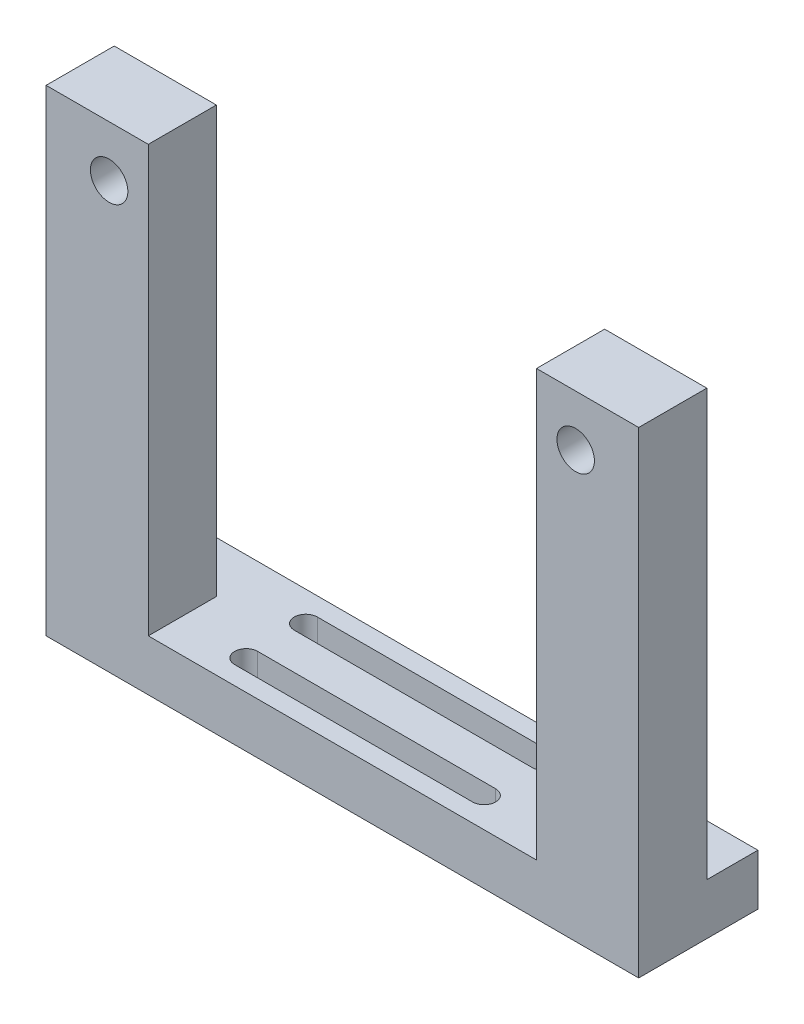
SolidWorks part; units mm, degrees
material "ABS"
ref_plane "前视基准面" through (0, 0, 0) normal (0, 0, 1) x (1, 0, 0)
ref_plane "上视基准面" through (0, 0, 0) normal (0, 1, 0) x (1, 0, 0)
ref_plane "右视基准面" through (0, 0, 0) normal (1, 0, 0) x (0, 0, -1)
other "Configuration Table"
sketch "草图1" plane through (0, 0, 0) normal (0, 0, 1) x (1, 0, 0)
  line L0 (-17.4, -11) -> (17.4, -11)
  line L1 (-11.4, 14) -> (11.4, 14)
  line L2 (-11.4, 14) -> (-11.4, -14)
  line L3 (-11.4, -14) -> (11.4, -14)
  line L4 (11.4, 14) -> (11.4, -14)
  line L5 (-11.4, 14) -> (11.4, -14) construction
  line L6 (-11.4, -14) -> (11.4, 14) construction
  line L7 (-17.4, 14) -> (17.4, 14)
  line L8 (-17.4, 14) -> (-17.4, -14)
  line L9 (-17.4, -14) -> (17.4, -14)
  line L10 (17.4, 14) -> (17.4, -14)
  line L11 (-17.4, 14) -> (17.4, -14) construction
  line L12 (-17.4, -14) -> (17.4, 14) construction
  point P0 (0, 0)
  point P5 (0, 0)
  dimension "D1" = 22.8
  dimension "D2" = 28
  dimension "D3" = 6
  dimension "D4" = 3
extrude "凸台-拉伸1" add sketch "草图1" along normal blind 4 contours L7 L8 L0 L2 | L8 L9 L2 L0 | L4 L0 L2 L3 | L10 L0 L4 L9 | L10 L7 L4 L0
sketch "草图3" plane through (0, 0, 0) normal (0, 0, -1) x (-1, 0, 0)
  line L0 (0, 15.0676) -> (0, -5.1843) construction
  line L4 (-11.4, 14) -> (-17.4, 14) construction
  circle A0 centre (-13.7, 11) radius 1.1
  circle A1 centre (13.7, 11) radius 1.1
  dimension "D1" = 2.2
  dimension "D2" = 2.2
  dimension "D3" = 27.4
  dimension "D4" = 3
extrude "切除-拉伸2" cut sketch "草图3" against normal through all
sketch "草图4" plane through (0, -14, 0) normal (0, -1, 0) x (1, 0, 0)
  line L1 (-17.4, 0) -> (17.4, 0)
  line L2 (-17.4, 0) -> (-17.4, -3)
  line L3 (-17.4, -3) -> (17.4, -3)
  line L4 (17.4, 0) -> (17.4, -3)
  dimension "D1" = 3
extrude "凸台-拉伸2" add sketch "草图4" against normal blind 3
sketch "草图5" plane through (0, -11, 0) normal (0, 1, 0) x (1, 0, 0)
  line L1 (6.5715, 1.25) -> (-7.4, 1.25) construction
  line L2 (6.5715, 0.575) -> (-7.4, 0.575)
  line L3 (6.5715, 1.925) -> (-7.4, 1.925)
  line L4 (-7.4, -2.25) -> (6.5715, -2.25) construction
  line L5 (-7.4, -1.575) -> (6.5715, -1.575)
  line L6 (-7.4, -2.925) -> (6.5715, -2.925)
  line L7 (-10.6986, -0.5) -> (12.8691, -0.5) construction
  line L8 (-17.4, 3) -> (17.4, 3) construction
  line L9 (-11.4, -4) -> (11.4, -4) construction
  line L10 (-11.4, -4) -> (-11.4, 0) construction
  line L11 (-7.4, 1.25) -> (-7.4, -0.5) construction
  line L12 (-7.4, 1.25) -> (-7.4, 3) construction
  arc A0 (6.5715, 0.575) -> (6.5715, 1.925) centre (6.5715, 1.25) ccw
  arc A1 (-7.4, 1.925) -> (-7.4, 0.575) centre (-7.4, 1.25) ccw
  arc A2 (-7.4, -1.575) -> (-7.4, -2.925) centre (-7.4, -2.25) ccw
  arc A3 (6.5715, -2.925) -> (6.5715, -1.575) centre (6.5715, -2.25) ccw
  spline S0 degree 3 poles (-1.0397, 0.6928) (-1.0178, 0.6933) (-0.9746, 0.6944) (-0.9112, 0.7034) (-0.8505, 0.718) (-0.7925, 0.7386) (-0.7372, 0.7651) (-0.6849, 0.7981) (-0.6348, 0.8362) (-0.5882, 0.8801) (-0.5454, 0.9285) (-0.5082, 0.9813) (-0.4766, 1.0378) (-0.4505, 1.0979) (-0.4304, 1.1619) (-0.4163, 1.2296) (-0.4078, 1.301) (-0.4067, 1.3499) (-0.4061, 1.3749) knots 0 0 0 0 0.063047 0.124207 0.183658 0.242406 0.300722 0.359831 0.419929 0.481518 0.543486 0.605372 0.666977 0.729505 0.793452 0.859465 0.928135 1 1 1 1 construction
  point P1 (-0.4143, 1.25)
  point P8 (-0.4143, -2.25)
  dimension "D1" = 1.35
  dimension "D3" = 4
extrude "切除-拉伸3" cut sketch "草图5" against normal through all
